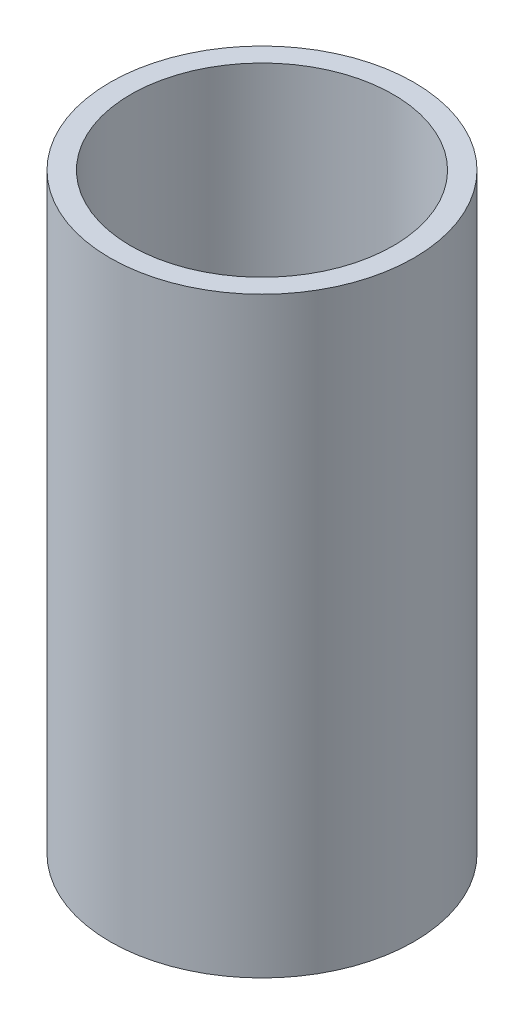
SolidWorks part; units mm, degrees
ref_plane "Front Plane" through (0, 0, 0) normal (0, 0, 1) x (1, 0, 0)
ref_plane "Top Plane" through (0, 0, 0) normal (0, 1, 0) x (1, 0, 0)
ref_plane "Right Plane" through (0, 0, 0) normal (1, 0, 0) x (0, 0, -1)
sketch "Sketch1" plane through (0, 0, 0) normal (0, 1, 0) x (1, 0, 0)
  circle A0 centre (0, 0) radius 4.1
  circle A1 centre (0, 0) radius 4.75
  dimension "D1" = 8.2
  dimension "D2" = 9.5
extrude "Boss-Extrude1" add sketch "Sketch1" along normal blind 18.5
